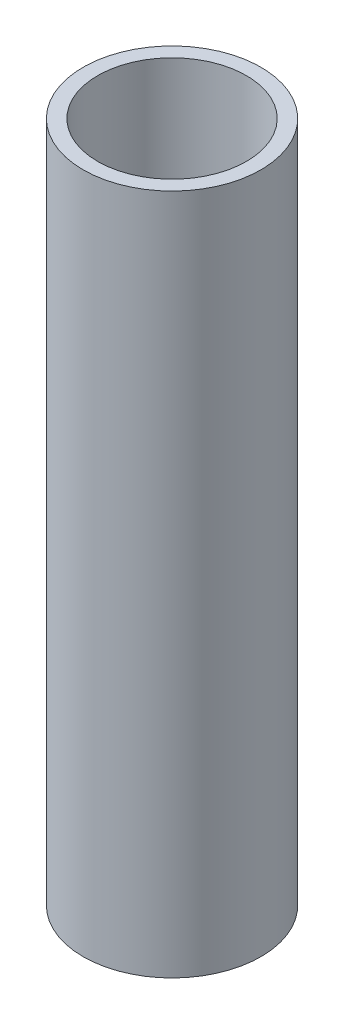
SolidWorks part; units mm, degrees
material "PVC Rigid"
ref_plane "Front Plane" through (0, 0, 0) normal (0, 0, 1) x (1, 0, 0)
ref_plane "Top Plane" through (0, 0, 0) normal (0, 1, 0) x (1, 0, 0)
ref_plane "Right Plane" through (0, 0, 0) normal (1, 0, 0) x (0, 0, -1)
sketch "Sketch1" plane through (0, 0, 0) normal (0, 1, 0) x (1, 0, 0)
  circle A0 centre (0, 0) radius 20.193
  circle A1 centre (0, 0) radius 24.13
  dimension "D1" = 48.26
  dimension "D2" = 40.386
extrude "Boss-Extrude1" add sketch "Sketch1" along normal blind 185
